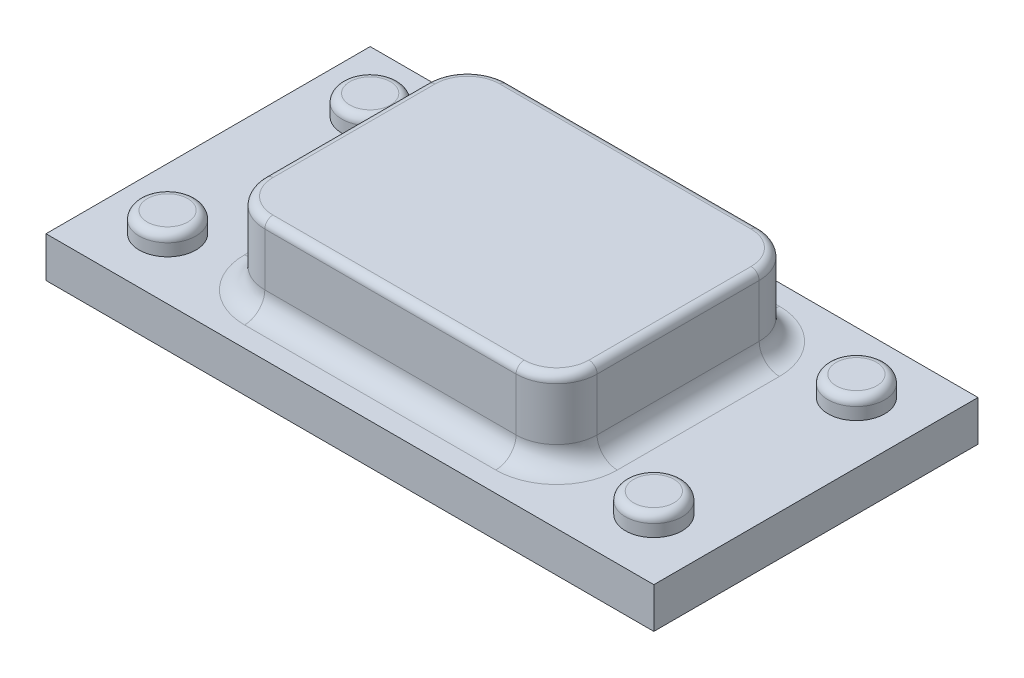
SolidWorks part; units mm, degrees
ref_plane "Front Plane" through (0, 0, 0) normal (0, 0, 1) x (1, 0, 0)
ref_plane "Top Plane" through (0, 0, 0) normal (0, 1, 0) x (1, 0, 0)
ref_plane "Right Plane" through (0, 0, 0) normal (1, 0, 0) x (0, 0, -1)
sketch "Sketch1" plane through (0, 0, 0) normal (0, 1, 0) x (1, 0, 0)
  line L1 (-75, 40) -> (75, 40)
  line L2 (-75, 40) -> (-75, -40)
  line L3 (-75, -40) -> (75, -40)
  line L4 (75, 40) -> (75, -40)
  line L5 (-75, 40) -> (75, -40) construction
  line L6 (-75, -40) -> (75, 40) construction
  point P0 (0, 0)
  dimension "D1" = 150
  dimension "D2" = 80
extrude "Boss-Extrude1" add sketch "Sketch1" along normal blind 10
sketch "Sketch2" plane through (0, 10, 0) normal (0, 1, 0) x (1, 0, 0)
  line L0 (0, 0) -> (0, 40) construction
  line L1 (75, 40) -> (-75, 40) construction
  line L2 (0, 40) -> (0, -40) construction
  line L3 (-75, -40) -> (75, -40) construction
  line L4 (-75, 40) -> (-75, -40) construction
  circle A0 centre (-60, 25) radius 7
  circle A1 centre (-60, -25) radius 7
  circle A2 centre (60, -25) radius 7
  circle A3 centre (60, 25) radius 7
  dimension "D1" = 14
  dimension "D2" = 14
  dimension "D3" = 15
  dimension "D4" = 15
  dimension "D5" = 15
  dimension "D6" = 15
extrude "Boss-Extrude2" add sketch "Sketch2" along normal blind 5
fillet "Fillet1" radius 2 4 edges at (-60, 15, 32) (60, 15, 18) (60, 15, -32) (-60, 15, -18)
sketch "Sketch3" plane through (0, 10, 0) normal (0, 1, 0) x (1, 0, 0)
  line L1 (-31, 30) -> (31, 30)
  line L2 (-41, 20) -> (-41, -20)
  line L3 (-31, -30) -> (31, -30)
  line L4 (41, 20) -> (41, -20)
  line L5 (-41, 30) -> (41, -30) construction
  line L6 (-41, -30) -> (41, 30) construction
  arc A0 (-41, -20) -> (-31, -30) centre (-31, -20) ccw
  arc A1 (31, 30) -> (41, 20) centre (31, 20) cw
  arc A2 (31, -30) -> (41, -20) centre (31, -20) ccw
  arc A3 (-31, 30) -> (-41, 20) centre (-31, 20) ccw
  point P0 (0, 0)
  dimension "D3" = 10
  dimension "D1" = 82
  dimension "D2" = 60
extrude "Boss-Extrude3" add sketch "Sketch3" along normal blind 20
fillet "Fillet2" radius 2 8 edges at (-41, 30, 0) (-38.0711, 30, -27.0711) (0, 30, -30) (38.0711, 30, -27.0711) (41, 30, 0) (38.0711, 30, 27.0711) (0, 30, 30) (-38.0711, 30, 27.0711)
fillet "Fillet3" radius 5 8 edges at (38.0711, 10, -27.0711) (41, 10, 0) (38.0711, 10, 27.0711) (0, 10, 30) (-38.0711, 10, 27.0711) (-41, 10, 0) (-38.0711, 10, -27.0711) (0, 10, -30)
sketch "Orientation Sketch" plane through (0, 10, 0) normal (0, 1, 0) x (1, 0, 0)
  line L0 (-31, 35) -> (31, 35) construction
  line L1 (46, 20) -> (46, -20) construction
  line L2 (31, -35) -> (-31, -35) construction
  line L3 (-46, -20) -> (-46, 20) construction
  line L4 (75, -40) -> (75, 40) construction
  line L5 (75, 40) -> (-75, 40) construction
  line L6 (-75, 40) -> (-75, -40) construction
  line L7 (-75, -40) -> (75, -40) construction
  line L8 (-31, 35) -> (31, 35)
  line L9 (46, 20) -> (46, -20)
  line L10 (31, -35) -> (-31, -35)
  line L11 (-46, -20) -> (-46, 20)
  line L12 (75, -40) -> (75, 40) construction
  line L13 (75, 40) -> (-75, 40) construction
  line L14 (-75, 40) -> (-75, -40) construction
  line L15 (-75, -40) -> (75, -40) construction
  arc A0 (46, 20) -> (31, 35) centre (31, 20) ccw construction
  arc A1 (31, -35) -> (46, -20) centre (31, -20) ccw construction
  arc A2 (-46, -20) -> (-31, -35) centre (-31, -20) ccw construction
  arc A3 (-31, 35) -> (-46, 20) centre (-31, 20) ccw construction
  circle A4 centre (60, 25) radius 7 construction
  circle A5 centre (60, -25) radius 7 construction
  circle A6 centre (-60, -25) radius 7 construction
  circle A7 centre (-60, 25) radius 7 construction
  arc A8 (46, 20) -> (31, 35) centre (31, 20) ccw
  arc A9 (31, -35) -> (46, -20) centre (31, -20) ccw
  arc A10 (-46, -20) -> (-31, -35) centre (-31, -20) ccw
  arc A11 (-31, 35) -> (-46, 20) centre (-31, 20) ccw
  circle A12 centre (60, 25) radius 7
  circle A13 centre (60, -25) radius 7
  circle A14 centre (-60, -25) radius 7
  circle A15 centre (-60, 25) radius 7
  point P14 (0, 0)
other "FormTool1"
